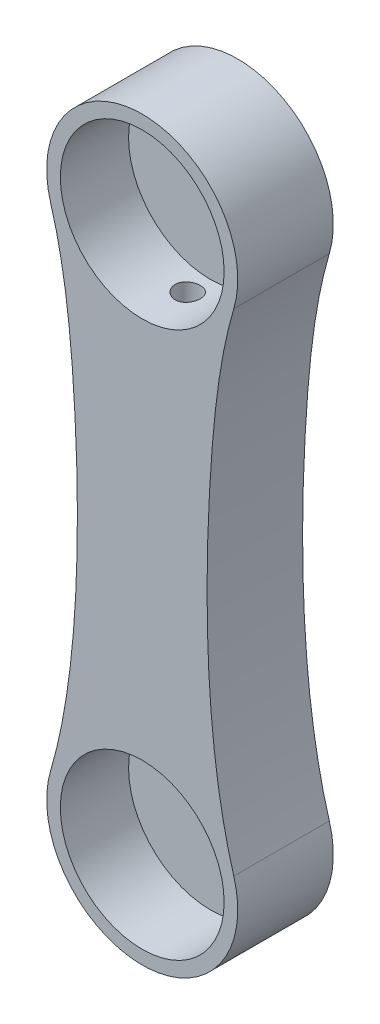
SolidWorks part; units mm, degrees
ref_plane "Front Plane" through (0, 0, 0) normal (0, 0, 1) x (1, 0, 0)
ref_plane "Top Plane" through (0, 0, 0) normal (0, 1, 0) x (1, 0, 0)
ref_plane "Right Plane" through (0, 0, 0) normal (1, 0, 0) x (0, 0, -1)
sketch "Sketch1" plane through (0, 0, 0) normal (0, 0, 1) x (1, 0, 0)
  circle A0 centre (0, 0) radius 21
  circle A1 centre (0, 120) radius 21
  dimension "D1" = 42
  dimension "D2" = 42
  dimension "D3" = 120
extrude "Boss-Extrude2" add sketch "Sketch1" along normal blind 5 contours A1 | A0
sketch "Sketch5" plane through (0, 0, 5) normal (0, 0, 1) x (1, 0, 0)
  line L0 (-21, 120) -> (-21, 0)
  line L1 (21, 0) -> (21, 120)
  line L2 (0, 120) -> (0, 107.3475) construction
  circle A0 centre (0, 120) radius 21 construction
  circle A1 centre (0, 120) radius 21
  circle A2 centre (0, 120) radius 21
  circle A3 centre (0, 0) radius 21
  circle A4 centre (0, 0) radius 21
  spline S0 degree 3 poles (-20.1246, 114) (-17.0727, 103.7635) (-12.9542, 66.8976) (-14.1807, 25.9366) (-20.1246, 6) knots 0 0 0 0 0.316725 1 1 1 1
  spline S1 degree 3 poles (20.1246, 114) (17.0727, 103.7635) (12.9542, 66.8976) (14.1807, 25.9366) (20.1246, 6) knots 0 0 0 0 0.316725 1 1 1 1
  circle M3 centre (0, 120) radius 21
  dimension "D3" = 40
  dimension "D4" = 15
  dimension "D5" = 6
  dimension "D1" = 0
  dimension "D2" = 0
extrude "Boss-Extrude5" add sketch "Sketch5" along normal blind 16 contours A4 L1 L0 M3 | M3 | A4
ref_plane "Plane1" through (0, 0, 6) normal (0, 0, -1) x (-1, 0, 0)
sketch "Sketch8" plane through (0, 0, 6) normal (0, 0, -1) x (-1, 0, 0)
  circle A2 centre (0, 120) radius 18
  circle A3 centre (0, 120) radius 18
  circle A5 centre (0, 0) radius 18
  circle A6 centre (0, 0) radius 18
  dimension "D1" = 3
  dimension "D2" = 3
extrude "Cut-Extrude3" cut sketch "Sketch8" against normal through all
sketch "Sketch9" plane through (0, 0, 5) normal (0, 0, -1) x (-1, 0, 0)
  arc A2 (-20.1246, 114) -> (20.1246, 114) centre (0, 120) ccw
  arc A3 (20.1246, 6) -> (-20.1246, 6) centre (0, 0) ccw
  arc A4 (-20.1246, 114) -> (20.1246, 114) centre (0, 120) ccw
  arc A5 (20.1246, 6) -> (-20.1246, 6) centre (0, 0) ccw
  spline S2 degree 3 poles (-4075.3941, -2786.9065) (-149.9219, 344.091) (125.554, 146.2742) (-156.8696, -478.9967) (-1938.6171, 4607.9259) knots -4.274152 -4.274152 -4.274152 -4.274152 0.316725 5.942453 5.942453 5.942453 5.942453 only from (-20.1246, 114) to (-20.1246, 6)
  spline S3 degree 3 poles (1938.6962, 4608.1517) (156.8742, -479.0068) (-125.5559, 146.272) (149.9213, 344.0906) (4075.3697, -2786.8871) knots -4.942536 -4.942536 -4.942536 -4.942536 0.683275 5.274142 5.274142 5.274142 5.274142 only from (20.1246, 6) to (20.1246, 114)
  spline S4 degree 3 poles (-20.1246, 114) (-17.0727, 103.7635) (-12.9542, 66.8976) (-14.1807, 25.9366) (-20.1246, 6) knots 0 0 0 0 0.316725 1 1 1 1
  spline S5 degree 3 poles (20.1246, 6) (14.1807, 25.9366) (12.9542, 66.8976) (17.0727, 103.7635) (20.1246, 114) knots 0 0 0 0 0.683275 1 1 1 1
  dimension "D1" = 0
extrude "Boss-Extrude6" add sketch "Sketch9" along normal up to surface (5 mm away) up to face at (21, 0, 0)
sketch "Sketch10" plane through (0, 0, 0) normal (0, 1, 0) x (1, 0, 0)
  line L2 (21, 0) -> (-21, 0) construction
  circle A0 centre (0, -11) radius 2.75
  dimension "D1" = 5.5
  dimension "D2" = 11
extrude "Cut-Extrude4" cut sketch "Sketch10" along normal blind 114
